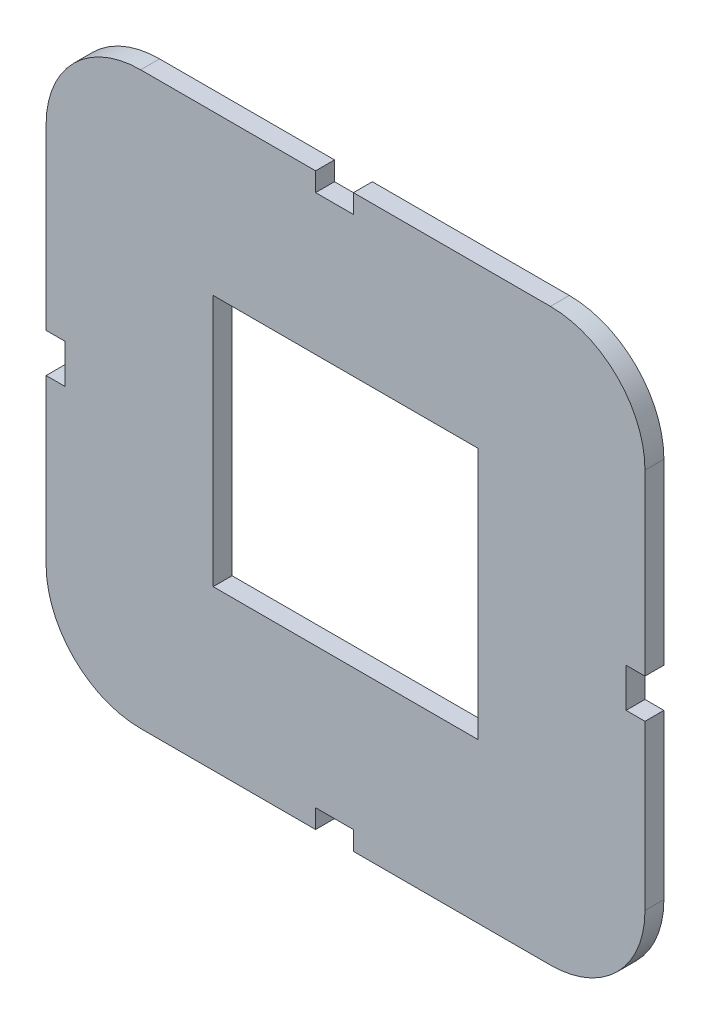
SolidWorks part; units mm, degrees
ref_plane "Front Plane" through (0, 0, 0) normal (0, 0, 1) x (1, 0, 0)
ref_plane "Top Plane" through (0, 0, 0) normal (0, 1, 0) x (1, 0, 0)
ref_plane "Right Plane" through (0, 0, 0) normal (1, 0, 0) x (0, 0, -1)
sketch "Sketch1" plane through (0, 0, 0) normal (0, 0, 1) x (1, 0, 0)
  line L0 (-47.5, -4.25) -> (-44.5, -4.25)
  line L1 (-32.5, -45.25) -> (-4.75, -45.25)
  line L2 (-47.5, -30.25) -> (-47.5, -4.25)
  line L3 (-32.5, 45.25) -> (-4.75, 45.25)
  line L4 (47.5, -30.25) -> (47.5, -4.25)
  line L5 (-47.5, -45.25) -> (47.5, 45.25) construction
  line L6 (-47.5, 45.25) -> (47.5, -45.25) construction
  line L7 (-44.5, -4.25) -> (-44.5, 1.95)
  line L8 (-44.5, 1.95) -> (-47.5, 1.95)
  line L9 (47.5, -4.25) -> (44.5, -4.25)
  line L10 (44.5, -4.25) -> (44.5, 1.95)
  line L11 (44.5, 1.95) -> (47.5, 1.95)
  line L12 (-1.75, 42.45) -> (-1.75, -48.05) construction
  line L13 (-44.5, -1.15) -> (44.5, -1.15) construction
  line L14 (-4.75, -45.25) -> (-4.75, -42.25)
  line L15 (-4.75, -42.25) -> (1.25, -42.25)
  line L16 (1.25, -42.25) -> (1.25, -45.25)
  line L17 (-4.75, 45.25) -> (-4.75, 42.25)
  line L18 (-4.75, 42.25) -> (1.25, 42.25)
  line L19 (1.25, 42.25) -> (1.25, 45.25)
  line L20 (-47.5, 1.95) -> (-47.5, 30.25)
  line L21 (1.25, 45.25) -> (32.5, 45.25)
  line L22 (47.5, 1.95) -> (47.5, 30.25)
  line L23 (1.25, -45.25) -> (32.5, -45.25)
  line L25 (21, 20.0053) -> (-21, 20.0053)
  line L26 (21, 20.0053) -> (21, -20.0053)
  line L27 (21, -20.0053) -> (-21, -20.0053)
  line L28 (-21, 20.0053) -> (-21, -20.0053)
  line L29 (21, 20.0053) -> (-21, -20.0053) construction
  line L30 (21, -20.0053) -> (-21, 20.0053) construction
  arc A0 (32.5, 45.25) -> (47.5, 30.25) centre (32.5, 30.25) cw
  arc A1 (32.5, -45.25) -> (47.5, -30.25) centre (32.5, -30.25) ccw
  arc A2 (-32.5, -45.25) -> (-47.5, -30.25) centre (-32.5, -30.25) cw
  arc A3 (-47.5, 30.25) -> (-32.5, 45.25) centre (-32.5, 30.25) cw
  point P0 (0, 0)
  point P27 (0, 0)
  dimension "D12" = 15
  dimension "D1" = 95
  dimension "D2" = 90.5
  dimension "D3" = 6.2
  dimension "D4" = 3
  dimension "D5" = 3
  dimension "D6" = 41
  dimension "D7" = 3
  dimension "D8" = 6
  dimension "D9" = 6
  dimension "D10" = 3
  dimension "D11" = 42
extrude "Boss-Extrude1" add sketch "Sketch1" along normal blind 3
